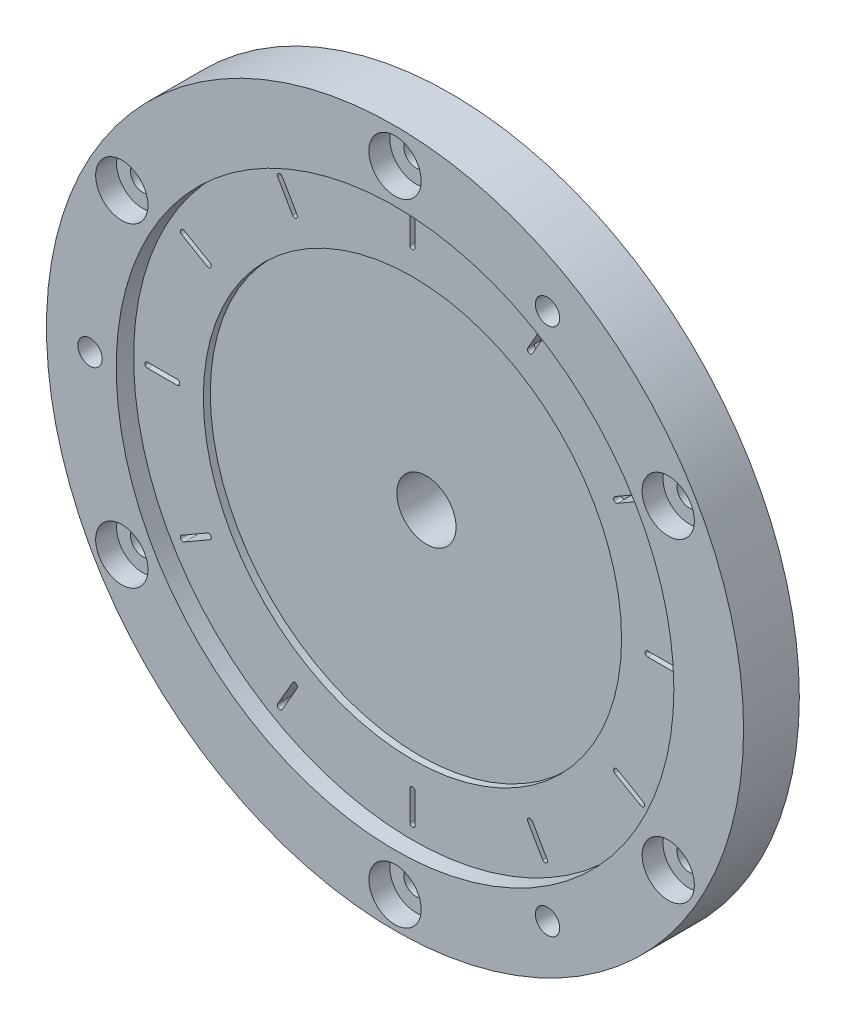
SolidWorks part; units mm, degrees
ref_plane "Front Plane" through (0, 0, 0) normal (0, 0, 1) x (1, 0, 0)
ref_plane "Top Plane" through (0, 0, 0) normal (0, 1, 0) x (1, 0, 0)
ref_plane "Right Plane" through (0, 0, 0) normal (1, 0, 0) x (0, 0, -1)
sketch "Sketch2" plane through (0, 0, 0) normal (0, 0, 1) x (1, 0, 0)
  circle A0 centre (0, 0) radius 200
  dimension "D1" = 400
extrude "Boss-Extrude1" add sketch "Sketch2" along normal blind 32
hole_wizard "CBORE for M5 Hex Head Bolt2" positions "Sketch6" profile "Sketch7" counterbore size "M5" standard "ISO" end condition through all
sketch "Sketch6" plane through (0, 0, 32) normal (0, 0, 1) x (1, 0, 0)
  line L0 (0, -1000) -> (0, 49000) construction
  circle A0 centre (0, 0) radius 180 construction
  point P0 (0, 180)
  dimension "D1" = 360
sketch "Sketch7" plane through (0, 180, 32) normal (1, 0, 0) x (0, -1, 0)
  line L0 (0, 0) -> (0, 32)
  line L1 (0, 32) -> (7, 32)
  line L3 (7, 32) -> (7, 12)
  line L4 (7, 12) -> (15, 12)
  line L5 (15, 12) -> (15, 0)
  line L7 (15, 0) -> (0, 0)
  line L11 (0, -6.35) -> (0, 107.95) construction
  dimension "Thru Hole Dia." = 14
  dimension "Thru Hole Depth" = 32
  dimension "C'Bore Dia." = 30
  dimension "C'Bore Depth" = 12
pattern_circular "CirPattern1" count 6 over 360 about axis through (0, -1.0182, 0) along (0, 0, 1) of "CBORE for M5 Hex Head Bolt2"
sketch "Sketch9" plane through (0, 0, 32) normal (0, 0, 1) x (1, 0, 0)
  line L0 (-1000, 0) -> (49000, 0) construction
  circle A0 centre (0, 0) radius 175
  circle A1 centre (-175, 0) radius 7
  circle A2 centre (87.5, 151.5544) radius 7
  circle A3 centre (87.5, -151.5544) radius 7
  point P13 (0, 0)
  dimension "D1" = 350
  dimension "D2" = 14
  dimension "D3" = 3
extrude "Cut-Extrude1" cut sketch "Sketch9" against normal through all contours A1 | A3 | A2
sketch "Sketch12" plane through (0, 0, 32) normal (0, 0, 1) x (1, 0, 0)
  circle A0 centre (0, 0) radius 160
  dimension "D1" = 320
extrude "Cut-Extrude7" cut sketch "Sketch12" against normal blind 10 contours A0
sketch "Sketch13" plane through (0, 0, 22) normal (0, 0, 1) x (1, 0, 0)
  circle A0 centre (0, 0) radius 120
  dimension "D1" = 240
extrude "Cut-Extrude8" cut sketch "Sketch13" against normal blind 4
sketch "Sketch15" plane through (0, 0, 0) normal (0, 0, -1) x (-1, 0, 0)
  line L0 (0, -135) -> (0, -152.0358) construction
  line L1 (1.5, -135) -> (1.5, -152.0358)
  line L2 (-1.5, -135) -> (-1.5, -152.0358)
  line L3 (-67.5, -116.9134) -> (-76.0179, -131.6668) construction
  line L4 (-66.201, -117.6634) -> (-74.7188, -132.4168)
  line L5 (-68.799, -116.1634) -> (-77.3169, -130.9168)
  line L6 (-116.9134, -67.5) -> (-131.6668, -76.0179) construction
  line L7 (-116.1634, -68.799) -> (-130.9168, -77.3169)
  line L8 (-117.6634, -66.201) -> (-132.4168, -74.7188)
  line L9 (-135, 0) -> (-152.0358, 0) construction
  line L10 (-135, -1.5) -> (-152.0358, -1.5)
  line L11 (-135, 1.5) -> (-152.0358, 1.5)
  line L12 (-116.9134, 67.5) -> (-131.6668, 76.0179) construction
  line L13 (-117.6634, 66.201) -> (-132.4168, 74.7188)
  line L14 (-116.1634, 68.799) -> (-130.9168, 77.3169)
  line L15 (-67.5, 116.9134) -> (-76.0179, 131.6668) construction
  line L16 (-68.799, 116.1634) -> (-77.3169, 130.9168)
  line L17 (-66.201, 117.6634) -> (-74.7188, 132.4168)
  line L18 (0, 135) -> (0, 152.0358) construction
  line L19 (-1.5, 135) -> (-1.5, 152.0358)
  line L20 (1.5, 135) -> (1.5, 152.0358)
  line L21 (67.5, 116.9134) -> (76.0179, 131.6668) construction
  line L22 (66.201, 117.6634) -> (74.7188, 132.4168)
  line L23 (68.799, 116.1634) -> (77.3169, 130.9168)
  line L24 (116.9134, 67.5) -> (131.6668, 76.0179) construction
  line L25 (116.1634, 68.799) -> (130.9168, 77.3169)
  line L26 (117.6634, 66.201) -> (132.4168, 74.7188)
  line L27 (135, 0) -> (152.0358, 0) construction
  line L28 (135, 1.5) -> (152.0358, 1.5)
  line L29 (135, -1.5) -> (152.0358, -1.5)
  line L30 (116.9134, -67.5) -> (131.6668, -76.0179) construction
  line L31 (117.6634, -66.201) -> (132.4168, -74.7188)
  line L32 (116.1634, -68.799) -> (130.9168, -77.3169)
  line L33 (67.5, -116.9134) -> (76.0179, -131.6668) construction
  line L34 (68.799, -116.1634) -> (77.3169, -130.9168)
  line L35 (66.201, -117.6634) -> (74.7188, -132.4168)
  circle A0 centre (0, 0) radius 135 construction
  arc A1 (1.5, -135) -> (-1.5, -135) centre (0, -135) ccw
  arc A2 (-1.5, -152.0358) -> (1.5, -152.0358) centre (0, -152.0358) ccw
  arc A3 (-66.201, -117.6634) -> (-68.799, -116.1634) centre (-67.5, -116.9134) ccw
  arc A4 (-77.3169, -130.9168) -> (-74.7188, -132.4168) centre (-76.0179, -131.6668) ccw
  arc A5 (-116.1634, -68.799) -> (-117.6634, -66.201) centre (-116.9134, -67.5) ccw
  arc A6 (-132.4168, -74.7188) -> (-130.9168, -77.3169) centre (-131.6668, -76.0179) ccw
  arc A7 (-135, -1.5) -> (-135, 1.5) centre (-135, 0) ccw
  arc A8 (-152.0358, 1.5) -> (-152.0358, -1.5) centre (-152.0358, 0) ccw
  arc A9 (-117.6634, 66.201) -> (-116.1634, 68.799) centre (-116.9134, 67.5) ccw
  arc A10 (-130.9168, 77.3169) -> (-132.4168, 74.7188) centre (-131.6668, 76.0179) ccw
  arc A11 (-68.799, 116.1634) -> (-66.201, 117.6634) centre (-67.5, 116.9134) ccw
  arc A12 (-74.7188, 132.4168) -> (-77.3169, 130.9168) centre (-76.0179, 131.6668) ccw
  arc A13 (-1.5, 135) -> (1.5, 135) centre (0, 135) ccw
  arc A14 (1.5, 152.0358) -> (-1.5, 152.0358) centre (0, 152.0358) ccw
  arc A15 (66.201, 117.6634) -> (68.799, 116.1634) centre (67.5, 116.9134) ccw
  arc A16 (77.3169, 130.9168) -> (74.7188, 132.4168) centre (76.0179, 131.6668) ccw
  arc A17 (116.1634, 68.799) -> (117.6634, 66.201) centre (116.9134, 67.5) ccw
  arc A18 (132.4168, 74.7188) -> (130.9168, 77.3169) centre (131.6668, 76.0179) ccw
  arc A19 (135, 1.5) -> (135, -1.5) centre (135, 0) ccw
  arc A20 (152.0358, -1.5) -> (152.0358, 1.5) centre (152.0358, 0) ccw
  arc A21 (117.6634, -66.201) -> (116.1634, -68.799) centre (116.9134, -67.5) ccw
  arc A22 (130.9168, -77.3169) -> (132.4168, -74.7188) centre (131.6668, -76.0179) ccw
  arc A23 (68.799, -116.1634) -> (66.201, -117.6634) centre (67.5, -116.9134) ccw
  arc A24 (74.7188, -132.4168) -> (77.3169, -130.9168) centre (76.0179, -131.6668) ccw
  point P5 (0, -143.5179)
  point P15 (-71.7589, -124.2901)
  point P22 (-124.2901, -71.7589)
  point P29 (-143.5179, 0)
  point P36 (-124.2901, 71.7589)
  point P43 (-71.7589, 124.2901)
  point P50 (0, 143.5179)
  point P57 (71.7589, 124.2901)
  point P64 (124.2901, 71.7589)
  point P71 (143.5179, 0)
  point P78 (124.2901, -71.7589)
  point P85 (71.7589, -124.2901)
  point P90 (0, 0)
  dimension "D1" = 270
  dimension "D2" = 1.5
  dimension "D3" = 12
extrude "Cut-Extrude9" cut sketch "Sketch15" against normal through all
sketch "Sketch16" plane through (0, 0, 18) normal (0, 0, 1) x (1, 0, 0)
  circle A0 centre (0, 0) radius 135
  dimension "D1" = 270
extrude "Cut-Extrude10" cut sketch "Sketch16" against normal blind 4
sketch "Sketch17" plane through (0, 0, 0) normal (0, 0, -1) x (-1, 0, 0)
  circle A0 centre (0, 0) radius 32
  dimension "D1" = 64
extrude "Boss-Extrude2" add sketch "Sketch17" along normal blind 10
fillet "Fillet1" radius 6 1 edges at (32, 0, 0)
sketch "Sketch18" plane through (0, 0, -10) normal (0, 0, -1) x (-1, 0, 0)
  circle A0 centre (0, 0) radius 27
  dimension "D1" = 54
extrude "Boss-Extrude3" add sketch "Sketch18" along normal blind 98
sketch "Sketch20" plane through (0, 0, -108) normal (0, 0, -1) x (-1, 0, 0)
  circle A0 centre (0, 0) radius 21
  dimension "D1" = 42
extrude "Boss-Extrude4" add sketch "Sketch20" against normal blind 32
sketch "Sketch19" plane through (0, 0, -108) normal (0, 0, -1) x (-1, 0, 0)
  circle A0 centre (0, 0) radius 17
  dimension "D1" = 34
extrude "Cut-Extrude11" cut sketch "Sketch19" against normal blind 128
